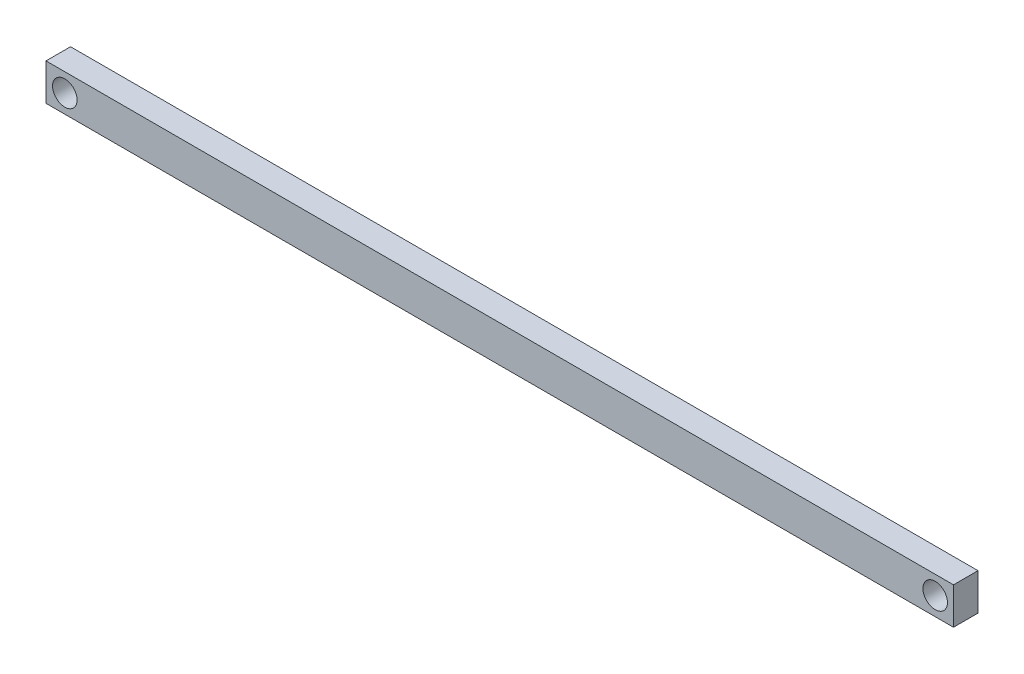
SolidWorks part; units mm, degrees
ref_plane "前视基准面" through (0, 0, 0) normal (0, 0, 1) x (1, 0, 0)
ref_plane "上视基准面" through (0, 0, 0) normal (0, 1, 0) x (1, 0, 0)
ref_plane "右视基准面" through (0, 0, 0) normal (1, 0, 0) x (0, 0, -1)
sketch "草图1" plane through (0, 0, 0) normal (0, 0, 1) x (1, 0, 0)
  line L1 (-52.5482, 6.0092) -> (317.4518, 6.0092)
  line L2 (-52.5482, 6.0092) -> (-52.5482, -8.9908)
  line L3 (-52.5482, -8.9908) -> (317.4518, -8.9908)
  line L4 (317.4518, 6.0092) -> (317.4518, -8.9908)
  circle A0 centre (-44.8667, -1.4908) radius 5
  circle A1 centre (309.9943, -1.4908) radius 5
  point P8 (339.6691, 0)
  point P9 (309.9943, -1.4908)
extrude "凸台-拉伸1" add sketch "草图1" along normal blind 10
